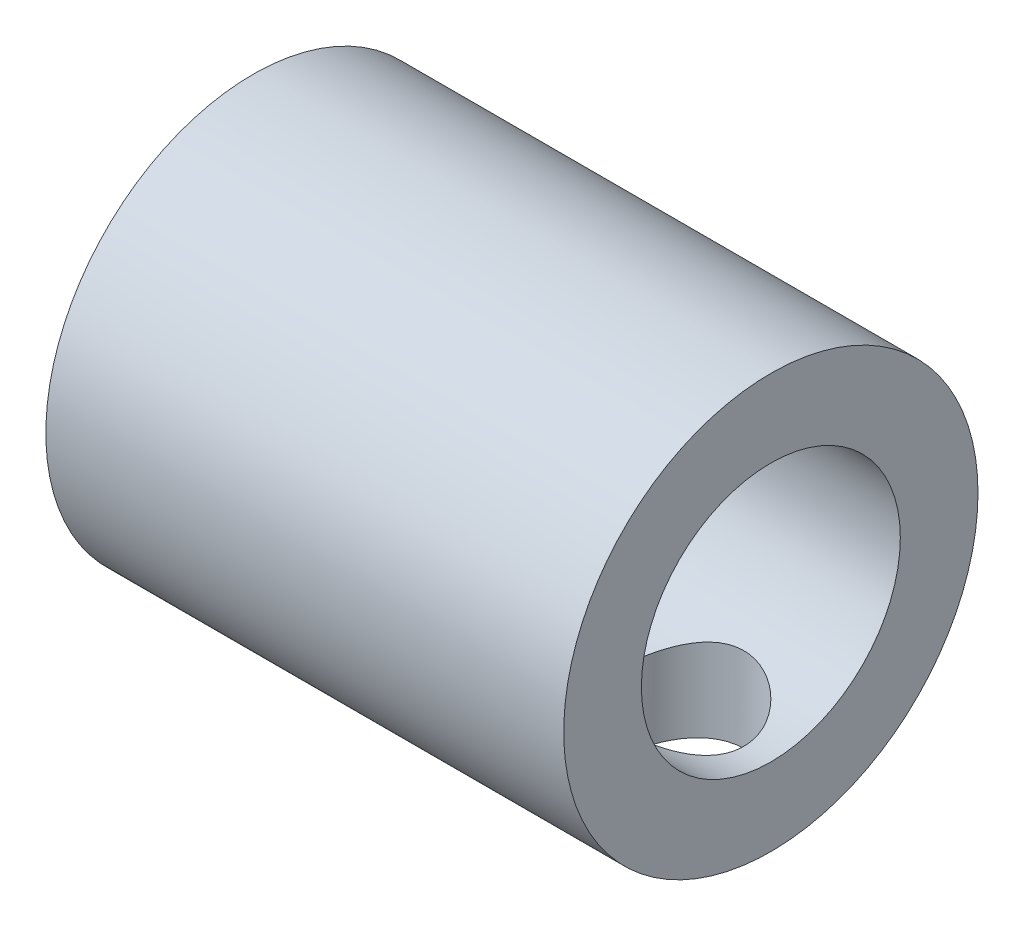
SolidWorks part; units mm, degrees
ref_plane "Front Plane" through (0, 0, 0) normal (0, 0, 1) x (1, 0, 0)
ref_plane "Top Plane" through (0, 0, 0) normal (0, 1, 0) x (1, 0, 0)
ref_plane "Right Plane" through (0, 0, 0) normal (1, 0, 0) x (0, 0, -1)
sketch "Sketch1" plane through (0, 0, 0) normal (1, 0, 0) x (0, 0, -1)
  circle A0 centre (0, 0) radius 7.62
  circle A1 centre (0, 0) radius 4.7625
  dimension "D1" = 9.525
  dimension "D2" = 15.24
extrude "Boss-Extrude1" add sketch "Sketch1" along normal blind 19.05
sketch "Sketch2" plane through (0, 0, 0) normal (0, 1, 0) x (1, 0, 0)
  line L0 (0, -7.62) -> (19.05, 7.62) construction
  line L1 (3.3952, 0) -> (15.6548, 0) construction
  circle A0 centre (15.6548, 0) radius 2.4016
  circle A1 centre (3.3952, 0) radius 2.4016
  point P6 (9.525, 0)
  point P7 (15.6548, 0)
  dimension "D1" = 4.8031
extrude "Cut-Extrude1" cut sketch "Sketch2" against normal up to surface (7.2317 mm away)
